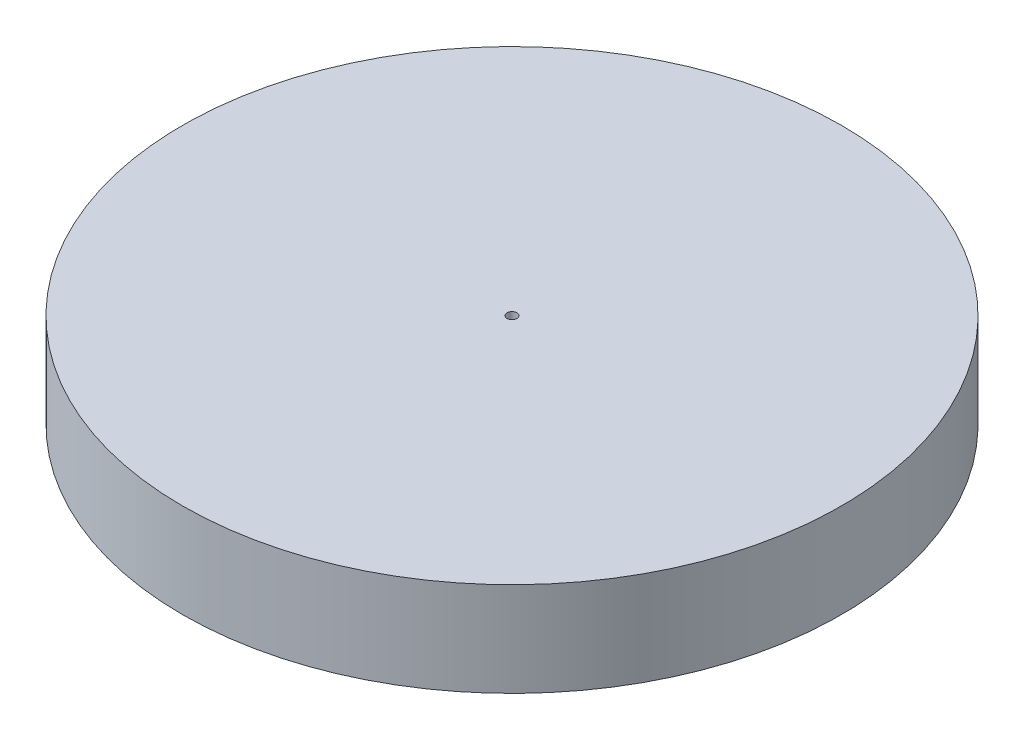
SolidWorks part; units mm, degrees
ref_plane "Front Plane" through (0, 0, 0) normal (0, 0, 1) x (1, 0, 0)
ref_plane "Top Plane" through (0, 0, 0) normal (0, 1, 0) x (1, 0, 0)
ref_plane "Right Plane" through (0, 0, 0) normal (1, 0, 0) x (0, 0, -1)
sketch "Sketch1" plane through (0, 0, 0) normal (0, 1, 0) x (1, 0, 0)
  circle A0 centre (0, 0) radius 105
  circle A1 centre (0, 0) radius 1.575
  dimension "D1" = 210
extrude "Extrude1" add sketch "Sketch1" along normal blind 30
